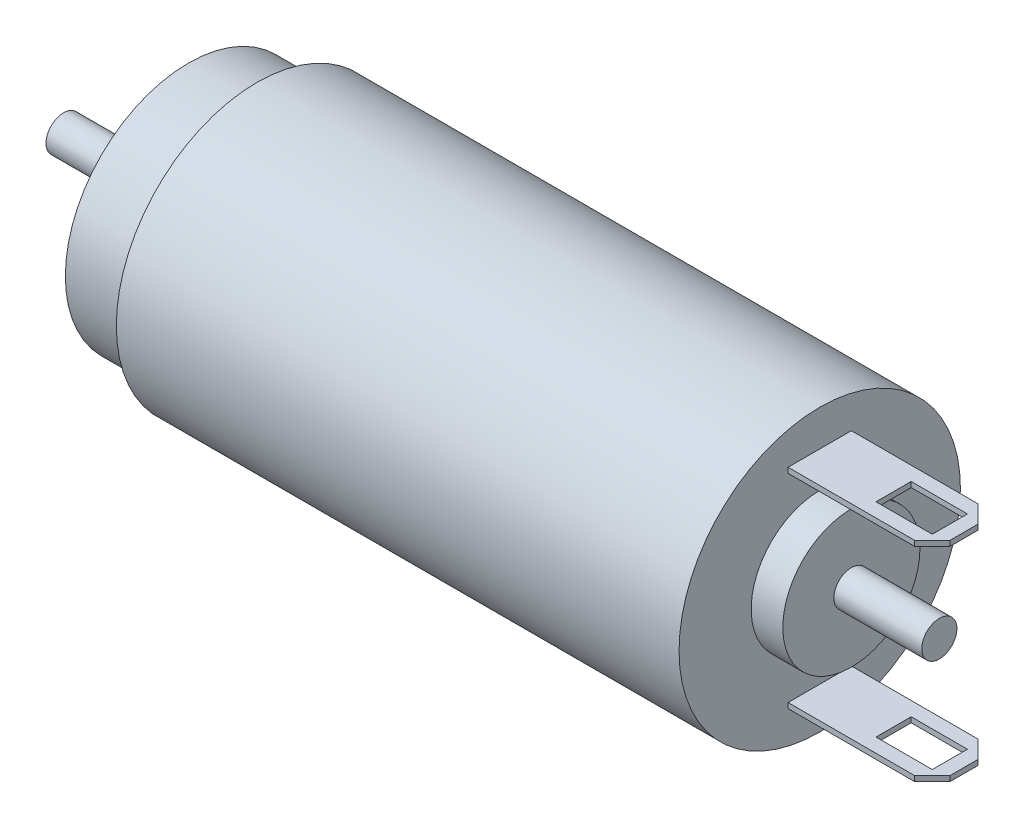
SolidWorks part; units mm, degrees
ref_plane "Plano frontal" through (0, 0, 0) normal (0, 0, 1) x (1, 0, 0)
ref_plane "Plano superior" through (0, 0, 0) normal (0, 1, 0) x (1, 0, 0)
ref_plane "Plano direito" through (0, 0, 0) normal (1, 0, 0) x (0, 0, -1)
sketch "Esboço1" plane through (0, 0, 0) normal (1, 0, 0) x (0, 0, -1)
  circle A0 centre (0, 0) radius 4
  dimension "D1" = 8
extrude "Ressalto-extrusão1" add sketch "Esboço1" against normal blind 16
sketch "Esboço2" plane through (-16, 0, 0) normal (-1, 0, 0) x (0, 0, 1)
  circle A0 centre (0, 0) radius 3.5
  dimension "D1" = 7
extrude "Ressalto-extrusão2" add sketch "Esboço2" along normal blind 1.95
sketch "Esboço3" plane through (-17.95, 0, 0) normal (-1, 0, 0) x (0, 0, 1)
  circle A0 centre (0, 0) radius 1.55
  dimension "D1" = 3.1
sketch "Esboço4" plane through (0, 0, 0) normal (1, 0, 0) x (0, 0, -1)
  circle A0 centre (0, 0) radius 1.95
  dimension "D1" = 3.9
extrude "Ressalto-extrusão4" add sketch "Esboço4" along normal blind 0.9
sketch "Esboço5" plane through (0.9, 0, 0) normal (1, 0, 0) x (0, 0, -1)
  circle A0 centre (0, 0) radius 0.5
  dimension "D1" = 1
extrude "Ressalto-extrusão5" add sketch "Esboço5" along normal blind 2.5
sketch "Esboço6" plane through (0, 0, 0) normal (1, 0, 0) x (0, 0, -1)
  line L4 (-0.9, 2.9717) -> (0.9, 2.9717)
  line L5 (0.9, 2.9717) -> (0.9, 2.8217)
  line L6 (0.9, 2.8217) -> (-0.9, 2.8217)
  line L7 (-0.9, 2.8217) -> (-0.9, 2.9717)
  dimension "D1" = 1.8
  dimension "D2" = 0.15
  dimension "D3" = 2.8217
  dimension "D4" = 0.9
extrude "Ressalto-extrusão6" add sketch "Esboço6" along normal blind 4.1
chamfer "Chanfro1" distance 0.5 angle 45 2 edges at (4.1, 2.8967, -0.9) (4.1, 2.8967, 0.9)
sketch "Esboço7" plane through (0, 2.9717, 0) normal (0, 1, 0) x (1, 0, 0)
  line L0 (3.6, 0.9) -> (0, 0.9) construction
  line L1 (2.1, 0.5) -> (3.7, 0.5)
  line L2 (2.1, 0.5) -> (2.1, -0.5)
  line L3 (2.1, -0.5) -> (3.7, -0.5)
  line L4 (3.7, 0.5) -> (3.7, -0.5)
  line L5 (4.1, 0.4) -> (4.1, -0.4) construction
  point P4 (2.1, 0)
  dimension "D1" = 0.4
  dimension "D2" = 0.4
  dimension "D3" = 1.6
extrude "Corte-extrusão1" cut sketch "Esboço7" against normal up to next
pattern_circular "PadrãoCircular1" count 2 every 180 about axis through (0, 0, 0) along (1, 0, 0) of "Chanfro1", "Ressalto-extrusão6", "Corte-extrusão1"
sketch "Esboço8" plane through (-17.95, 0, 0) normal (-1, 0, 0) x (0, 0, 1)
extrude "Corte-extrusão2" cut sketch "Esboço3" against normal blind 0.65
sketch "Esboço9" plane through (-17.3, 0, 0) normal (-1, 0, 0) x (0, 0, 1)
  circle A0 centre (0, 0) radius 0.5
  dimension "D1" = 1
extrude "Ressalto-extrusão7" add sketch "Esboço9" along normal blind 4.2
